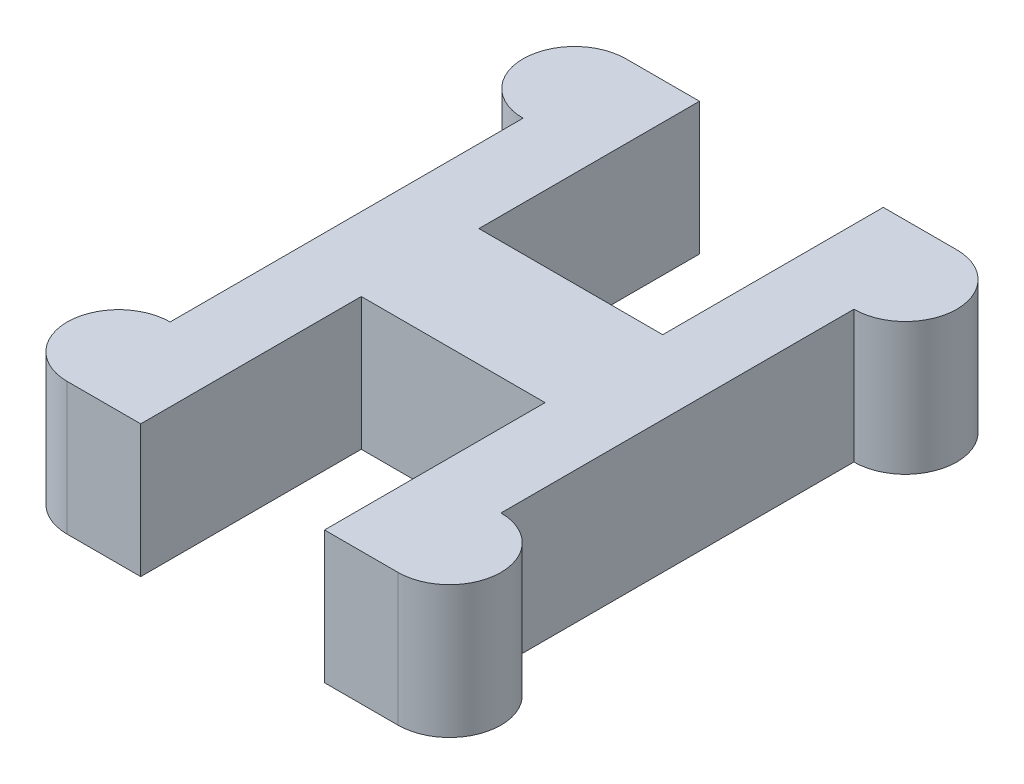
SolidWorks part; units mm, degrees
ref_plane "Front Plane" through (0, 0, 0) normal (0, 0, 1) x (1, 0, 0)
ref_plane "Top Plane" through (0, 0, 0) normal (0, 1, 0) x (1, 0, 0)
ref_plane "Right Plane" through (0, 0, 0) normal (1, 0, 0) x (0, 0, -1)
sketch "Sketch1" plane through (0, 0, 0) normal (0, 1, 0) x (1, 0, 0)
  line L0 (-2.25, 3.1) -> (2.25, 3.1) construction
  line L1 (-2.25, -3.8) -> (2.25, -3.8)
  line L2 (-2.25, -3.8) -> (-2.25, 3.8)
  line L3 (-2.25, 3.8) -> (2.25, 3.8)
  line L4 (2.25, -3.8) -> (2.25, 3.8)
  line L5 (-2.25, -3.8) -> (2.25, 3.8) construction
  line L6 (-2.25, 3.8) -> (2.25, -3.8) construction
  line L7 (-2.25, 3.8) -> (2.25, 3.8)
  line L8 (-2.25, 2.4) -> (2.25, 2.4)
  line L9 (-2.25, -3.1) -> (2.25, -3.1) construction
  line L10 (-2.25, -2.4) -> (2.25, -2.4)
  line L11 (-2.25, -3.8) -> (2.25, -3.8)
  line L13 (-1.25, 3.8) -> (1.25, 3.8)
  line L14 (-1.25, 3.8) -> (-1.25, 0.8)
  line L15 (-1.25, 0.8) -> (1.25, 0.8)
  line L16 (1.25, 3.8) -> (1.25, 0.8)
  line L17 (1.25, -3.8) -> (-1.25, -3.8)
  line L18 (1.25, -3.8) -> (1.25, -0.8)
  line L19 (1.25, -0.8) -> (-1.25, -0.8)
  line L20 (-1.25, -3.8) -> (-1.25, -0.8)
  arc A0 (-2.25, 3.8) -> (-2.25, 2.4) centre (-2.25, 3.1) ccw
  arc A1 (2.25, 2.4) -> (2.25, 3.8) centre (2.25, 3.1) ccw
  arc A2 (-2.25, -2.4) -> (-2.25, -3.8) centre (-2.25, -3.1) ccw
  arc A3 (2.25, -3.8) -> (2.25, -2.4) centre (2.25, -3.1) ccw
  point P0 (0, 0)
  point P8 (0, 3.1)
  point P15 (0, -3.1)
  point P28 (0, 0.8)
  point P29 (0, -0.8)
  dimension "D1" = 4.5
  dimension "D2" = 7.6
  dimension "D3" = 1.4
  dimension "D4" = 2.5
  dimension "D5" = 3
extrude "Boss-Extrude1" add sketch "Sketch1" along normal blind 1.8 contours L10 L20 L19 L18 L4 L8 L16 L15 L14 L2 | L14 L3 L2 L8 | L2 A0 | L3 L16 L8 L4 | L4 A1 | L4 A3 | L18 L1 L4 L10 | L1 L20 L10 L2 | L2 A2
